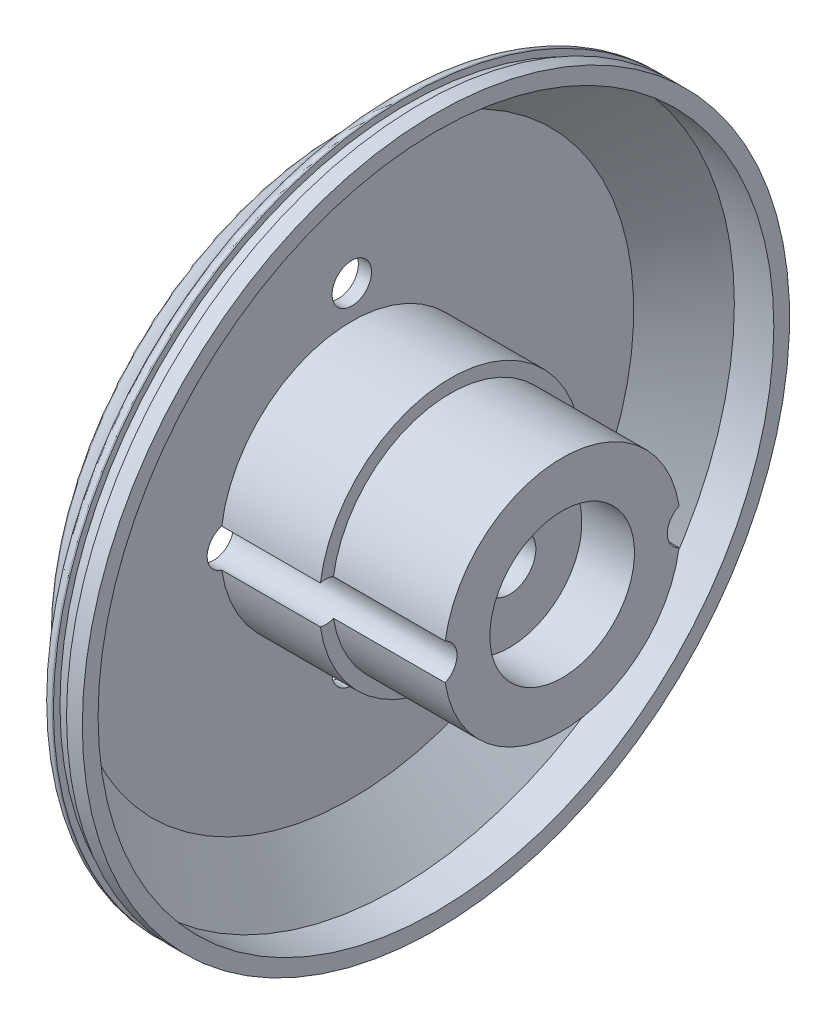
SolidWorks part; units mm, degrees
ref_plane "Front Plane" through (0, 0, 0) normal (0, 0, 1) x (1, 0, 0)
ref_plane "Top Plane" through (0, 0, 0) normal (0, 1, 0) x (1, 0, 0)
ref_plane "Right Plane" through (0, 0, 0) normal (1, 0, 0) x (0, 0, -1)
sketch "Sketch1" plane through (0, 0, 0) normal (0, 0, 1) x (1, 0, 0)
  line L0 (9.3645, 20.7387) -> (9.3645, -21.0613) construction
  line L1 (4, 2) -> (4, 5.5)
  line L2 (0, 5.5) -> (0, 22)
  line L3 (4.5, 26.9) -> (5.2, 26.9)
  line L4 (4.4, 25.7) -> (7.4, 25.7)
  line L5 (1, 10) -> (8.5, 10)
  line L6 (17, 9) -> (17, 5.5)
  line L7 (6.2, 26.9) -> (6.2, 26.4)
  line L8 (13, 2) -> (4, 2)
  line L9 (1, 21.4469) -> (4.4, 25.7)
  line L10 (7.4, 25.7) -> (7.4, 26.9)
  line L11 (1, 21.4469) -> (1, 10)
  line L12 (0, 0) -> (35.5, 0) construction
  line L13 (4, 5.5) -> (0, 5.5)
  line L14 (-37.6185, 20.7402) -> (-37.6185, 19.2402) construction
  line L15 (-37.6185, 15.1784) -> (-5.0714, 15.1784) construction
  line L16 (17, 9) -> (8.5, 9)
  line L17 (8.5, 9) -> (8.5, 10)
  line L18 (17, 5.5) -> (13, 5.5)
  line L19 (13, 5.5) -> (13, 2)
  line L20 (6.2, 26.4) -> (5.2, 26.4)
  line L21 (5.2, 26.4) -> (5.2, 26.9)
  line L22 (6.2, 26.9) -> (7.4, 26.9)
  arc A0 (0, 22) -> (4.5, 26.9) centre (-6.1834, 32.1949) ccw
  dimension "D4" = 9
  dimension "D1" = 41.8
  dimension "D2" = 35.5
  dimension "D3" = 1.5
  dimension "D5" = 1.2
  dimension "D6" = 22
  dimension "D7" = 5.5
  dimension "D8" = 10
  dimension "D9" = 1
  dimension "D10" = 4.5
  dimension "D11" = 3
  dimension "D12" = 1.2
  dimension "D13" = 4
  dimension "D14" = 26.9
  dimension "D15" = 4.5
  dimension "D16" = 0.5
  dimension "D17" = 17
  dimension "D18" = 2
  dimension "D19" = 1
  dimension "D20" = 0.7
  dimension "D21" = 0.5531
revolve "Revolve1" add sketch "Sketch1" angle 360 about L12
fillet "Fillet1" radius 1 2 edges at (4.5, 0, 26.9) (0, 0, 22)
sketch "Sketch3" plane through (0, 0, 0) normal (-1, 0, 0) x (0, 0, 1)
  line L0 (0, 0) -> (0, 18.5597) construction
  line L1 (0, 0) -> (-18.673, 18.673) construction
  line L2 (0, 0) -> (16.4085, 16.4085) construction
  line L3 (0, 0) -> (6.2748, 0) construction
  arc A0 (-8.6539, 25.47) -> (8.6539, 25.47) centre (0, 0) cw
  circle A1 centre (0, 0) radius 26.9 construction
  arc A2 (11.8908, 24.1292) -> (24.1292, 11.8908) centre (0, 0) cw
  arc A3 (25.47, 8.6539) -> (25.47, -8.6539) centre (0, 0) cw
  arc A4 (24.1292, -11.8908) -> (11.8908, -24.1292) centre (0, 0) cw
  arc A5 (6.8027, -4.2099) -> (13.6053, -8.4199) centre (10.204, -6.3149) cw
  arc A6 (6.8027, -4.2099) -> (4.2099, -6.8027) centre (0, 0) cw
  arc A7 (4.2099, -6.8027) -> (8.4199, -13.6053) centre (6.3149, -10.204) ccw
  arc A8 (13.6053, -8.4199) -> (8.4199, -13.6053) centre (0, 0) cw
  arc A9 (-4.2099, -6.8027) -> (-8.4199, -13.6053) centre (-6.3149, -10.204) cw
  arc A10 (-4.2099, -6.8027) -> (-6.8027, -4.2099) centre (0, 0) cw
  arc A17 (-6.8027, -4.2099) -> (-13.6053, -8.4199) centre (-10.204, -6.3149) ccw
  arc A18 (-8.4199, -13.6053) -> (-13.6053, -8.4199) centre (0, 0) cw
  arc A19 (-6.8027, 4.2099) -> (-13.6053, 8.4199) centre (-10.204, 6.3149) cw
  arc A20 (-6.8027, 4.2099) -> (-4.2099, 6.8027) centre (0, 0) cw
  arc A21 (-4.2099, 6.8027) -> (-8.4199, 13.6053) centre (-6.3149, 10.204) ccw
  arc A22 (8.6539, -25.47) -> (-8.6539, -25.47) centre (0, 0) cw
  arc A23 (-13.6053, 8.4199) -> (-8.4199, 13.6053) centre (0, 0) cw
  arc A24 (-11.8908, -24.1292) -> (-24.1292, -11.8908) centre (0, 0) cw
  arc A25 (-25.47, -8.6539) -> (-25.47, 8.6539) centre (0, 0) cw
  arc A26 (-24.1292, 11.8908) -> (-11.8908, 24.1292) centre (0, 0) cw
  arc A29 (4.2099, 6.8027) -> (6.8027, 4.2099) centre (0, 0) cw
  arc A30 (8.4199, 13.6053) -> (13.6053, 8.4199) centre (0, 0) cw
  arc A31 (4.2099, 6.8027) -> (8.4199, 13.6053) centre (6.3149, 10.204) cw
  arc A32 (6.8027, 4.2099) -> (13.6053, 8.4199) centre (10.204, 6.3149) ccw
  circle A37 centre (0, 12.5) radius 1.5
  circle A38 centre (-9.5, 0) radius 1.5
  circle A39 centre (9.5, 0) radius 1.5
  circle A40 centre (0, -12.5) radius 1.5
  ellipse E0 centre (0, 29.4609) end of major axis (0, 17.0494) minor radius 9.1392 (-8.6539, 25.47) -> (8.6539, 25.47) ccw
  ellipse E1 centre (20.832, 20.832) end of major axis (12.7469, 12.7469) minor radius 9.2346 (11.8908, 24.1292) -> (24.1292, 11.8908) ccw
  ellipse E2 centre (29.4609, 0) end of major axis (40.895, 0) minor radius 9.2346 (25.47, 8.6539) -> (25.47, -8.6539) ccw
  ellipse E3 centre (20.832, -20.832) end of major axis (28.9171, -28.9171) minor radius 9.2346 (24.1292, -11.8908) -> (11.8908, -24.1292) ccw
  ellipse E4 centre (0, -29.4609) end of major axis (0, -40.895) minor radius 9.2346 (8.6539, -25.47) -> (-8.6539, -25.47) ccw
  ellipse E5 centre (-20.832, -20.832) end of major axis (-12.7469, -12.7469) minor radius 9.2346 (-11.8908, -24.1292) -> (-24.1292, -11.8908) ccw
  ellipse E6 centre (-29.4609, 0) end of major axis (-18.0269, 0) minor radius 9.2346 (-25.47, -8.6539) -> (-25.47, 8.6539) ccw
  ellipse E7 centre (-20.832, 20.832) end of major axis (-29.6083, 29.6083) minor radius 9.1392 (-24.1292, 11.8908) -> (-11.8908, 24.1292) ccw
  point P36 (0, 0)
  point P74 (0, 0)
  point P80 (0, 0)
  point P140 (0, 0)
  dimension "D2" = 8
  dimension "D4" = 4
  dimension "D6" = 16
  dimension "D8" = 5.5
  dimension "D12" = 3
  dimension "D3" = 45
  dimension "D7" = 45
  dimension "D13" = 25
  dimension "D14" = 19
  dimension "D5" = 8
chamfer "Chamfer2" [suppressed] distance 0.5 angle 45
extrude "Cut-Extrude2" cut sketch "Sketch3" against normal through all contours A38 | A37 | A39 | A40
